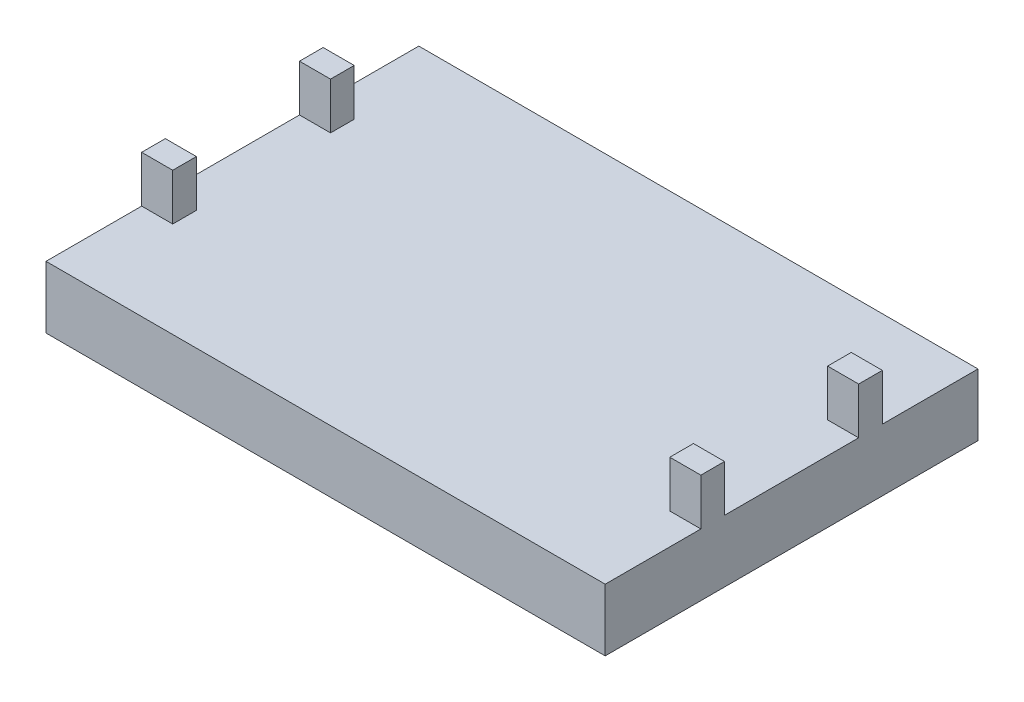
SolidWorks part; units mm, degrees
ref_plane "Front Plane" through (0, 0, 0) normal (0, 0, 1) x (1, 0, 0)
ref_plane "Top Plane" through (0, 0, 0) normal (0, 1, 0) x (1, 0, 0)
ref_plane "Right Plane" through (0, 0, 0) normal (1, 0, 0) x (0, 0, -1)
sketch "Sketch1" plane through (0, 0, 0) normal (0, 1, 0) x (1, 0, 0)
  line L1 (45, -30) -> (-45, -30)
  line L2 (45, -30) -> (45, 30)
  line L3 (45, 30) -> (-45, 30)
  line L4 (-45, -30) -> (-45, 30)
  line L5 (45, -30) -> (-45, 30) construction
  line L6 (45, 30) -> (-45, -30) construction
  point P0 (0, 0)
  dimension "D1" = 60
  dimension "D2" = 90
extrude "Boss-Extrude1" add sketch "Sketch1" along normal blind 10
sketch "Sketch2" plane through (0, 0, 0) normal (0, -1, 0) x (1, 0, 0)
  line L5 (45, -30) -> (-45, 30) construction
  line L6 (45, 30) -> (-45, -30) construction
  line L11 (-45, 30) -> (-35, 30)
  line L12 (-45, 30) -> (-45, 20)
  line L13 (-45, 20) -> (-35, 20)
  line L14 (-35, 30) -> (-35, 20)
  line L15 (-45, -30) -> (-35, -30)
  line L16 (-45, -30) -> (-45, -20)
  line L17 (-45, -20) -> (-35, -20)
  line L18 (-35, -30) -> (-35, -20)
  line L19 (35, -20) -> (45, -20)
  line L20 (35, -20) -> (35, -30)
  line L21 (35, -30) -> (45, -30)
  line L22 (45, -20) -> (45, -30)
  line L23 (35, 20) -> (45, 20)
  line L24 (35, 20) -> (35, 30)
  line L25 (35, 30) -> (45, 30)
  line L26 (45, 20) -> (45, 30)
  point P0 (0, 0)
sketch "Sketch4" plane through (-45, 0, 0) normal (-1, 0, 0) x (0, 0, 1)
  line L0 (0, 10) -> (0, 0)
  line L1 (-30, 10) -> (30, 10) construction
  line L2 (10.795, 10) -> (14.605, 10)
  line L3 (-14.605, 10) -> (-10.795, 10)
  line L4 (-14.605, 10) -> (14.605, 10) construction
  line L5 (14.605, 17.5) -> (14.605, 2.5)
  line L6 (14.605, 2.5) -> (10.795, 2.5)
  line L7 (10.795, 17.5) -> (10.795, 2.5)
  line L9 (-14.605, 17.5) -> (-14.605, 2.5)
  line L10 (-14.605, 2.5) -> (-10.795, 2.5)
  line L11 (-10.795, 17.5) -> (-10.795, 2.5)
  line L13 (14.605, 17.5) -> (10.795, 17.5)
  line L14 (-14.605, 17.5) -> (-10.795, 17.5)
  point P8 (0, 5)
  line M3 (30, 10) -> (-30, 10)
  dimension "D1" = 7.5
extrude "Boss-Extrude2" add sketch "Sketch4" against normal blind 5 contours L14 L9 L11 M3 | L5 L13 L7 M3
mirror "Mirror1" about plane through (0, 0, 0) normal (1, 0, 0) of "Boss-Extrude2"
